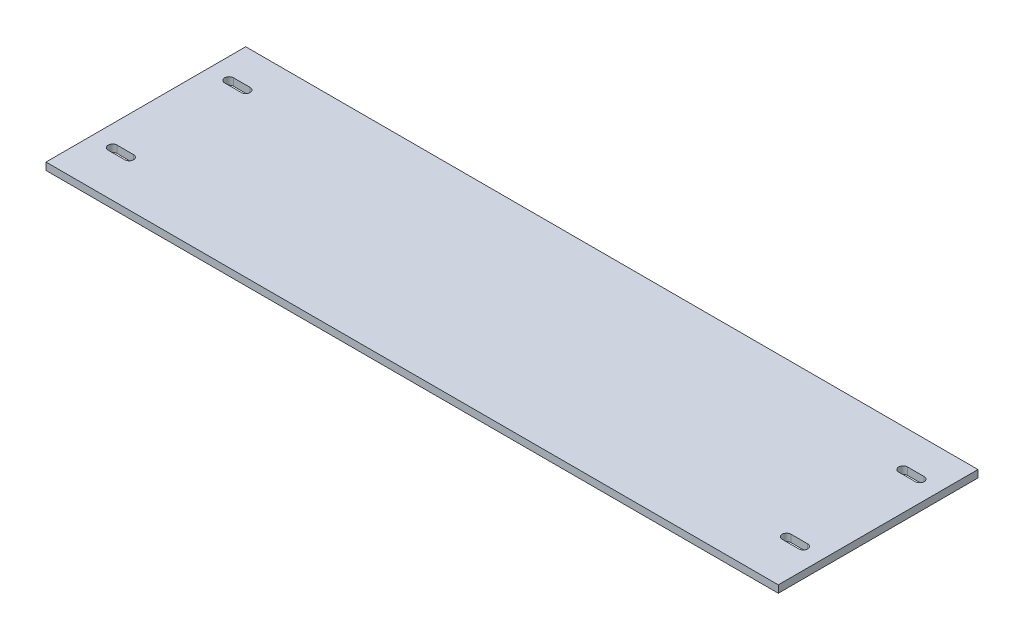
SolidWorks part; units mm, degrees
material "PC High Viscosity"
ref_plane "Front" through (0, 0, 0) normal (0, 0, 1) x (1, 0, 0)
ref_plane "Top" through (0, 0, 0) normal (0, 1, 0) x (1, 0, 0)
ref_plane "Right" through (0, 0, 0) normal (1, 0, 0) x (0, 0, -1)
sketch "Sketch1" plane through (0, 0, 0) normal (0, 1, 0) x (1, 0, 0)
  line L0 (15.875, 34.925) -> (28.575, 34.925) construction
  line L1 (0, 0) -> (558.8, 0)
  line L2 (0, 0) -> (0, 152.4)
  line L3 (0, 152.4) -> (558.8, 152.4)
  line L4 (558.8, 0) -> (558.8, 152.4)
  line L5 (15.875, 38.3032) -> (28.575, 38.3032)
  line L6 (15.875, 31.5468) -> (28.575, 31.5468)
  line L7 (22.225, 34.925) -> (22.225, 123.825) construction
  line L8 (15.875, 123.825) -> (28.575, 123.825) construction
  line L9 (15.875, 127.2032) -> (28.575, 127.2032)
  line L10 (15.875, 120.4468) -> (28.575, 120.4468)
  line L11 (22.225, 123.825) -> (66.675, 123.825) construction
  line L12 (66.675, 123.825) -> (66.675, 34.925) construction
  line L13 (66.675, 34.925) -> (22.225, 34.925) construction
  line L14 (60.325, 123.825) -> (73.025, 123.825) construction
  line L15 (60.325, 127.2032) -> (73.025, 127.2032) construction
  line L16 (60.325, 120.4468) -> (73.025, 120.4468) construction
  line L17 (60.325, 34.925) -> (73.025, 34.925) construction
  line L18 (60.325, 38.3032) -> (73.025, 38.3032) construction
  line L19 (60.325, 31.5468) -> (73.025, 31.5468) construction
  line L20 (536.575, 123.825) -> (536.575, 34.925) construction
  line L21 (542.925, 123.825) -> (530.225, 123.825) construction
  line L22 (542.925, 120.4468) -> (530.225, 120.4468)
  line L23 (542.925, 127.2032) -> (530.225, 127.2032)
  line L24 (542.925, 34.925) -> (530.225, 34.925) construction
  line L25 (542.925, 31.5468) -> (530.225, 31.5468)
  line L26 (542.925, 38.3032) -> (530.225, 38.3032)
  arc A0 (15.875, 38.3032) -> (15.875, 31.5468) centre (15.875, 34.925) ccw
  arc A1 (28.575, 31.5468) -> (28.575, 38.3032) centre (28.575, 34.925) ccw
  arc A2 (15.875, 127.2032) -> (15.875, 120.4468) centre (15.875, 123.825) ccw
  arc A3 (28.575, 120.4468) -> (28.575, 127.2032) centre (28.575, 123.825) ccw
  arc A4 (60.325, 127.2032) -> (60.325, 120.4468) centre (60.325, 123.825) ccw construction
  arc A5 (73.025, 120.4468) -> (73.025, 127.2032) centre (73.025, 123.825) ccw construction
  arc A6 (60.325, 38.3032) -> (60.325, 31.5468) centre (60.325, 34.925) ccw construction
  arc A7 (73.025, 31.5468) -> (73.025, 38.3032) centre (73.025, 34.925) ccw construction
  arc A8 (542.925, 120.4468) -> (542.925, 127.2032) centre (542.925, 123.825) ccw
  arc A9 (530.225, 127.2032) -> (530.225, 120.4468) centre (530.225, 123.825) ccw
  arc A10 (542.925, 31.5468) -> (542.925, 38.3032) centre (542.925, 34.925) ccw
  arc A11 (530.225, 38.3032) -> (530.225, 31.5468) centre (530.225, 34.925) ccw
  point P7 (22.225, 34.925)
  point P13 (22.225, 123.825)
  point P25 (66.675, 123.825)
  point P31 (66.675, 34.925)
  point P40 (536.575, 123.825)
  point P47 (536.575, 34.925)
  dimension "D1" = 6.7564
  dimension "D2" = 34.925
  dimension "D3" = 12.7
  dimension "D4" = 22.225
  dimension "D5" = 152.4
  dimension "D6" = 28.575
  dimension "D7" = 44.45
  dimension "D8" = 22.225
  dimension "D9" = 514.35
extrude "Boss-Extrude1" add sketch "Sketch1" along normal blind 5.588
fillet "Fillet1" [suppressed] radius 3.175
sketch "Sketch2" plane through (0, 5.588, 0) normal (0, 1, 0) x (1, 0, 0)
  line L0 (279.4, 152.4) -> (279.4, 0) construction
  line L1 (558.8, 152.4) -> (0, 152.4) construction
  line L2 (0, 0) -> (558.8, 0) construction
  line L4 (469.9, 25.4) -> (88.9, 25.4) construction
  line L5 (469.9, 25.4) -> (469.9, 127) construction
  line L6 (469.9, 127) -> (88.9, 127) construction
  line L7 (88.9, 25.4) -> (88.9, 127) construction
  line L8 (469.9, 25.4) -> (88.9, 127) construction
  line L9 (469.9, 127) -> (88.9, 25.4) construction
  circle A1 centre (88.9, 25.4) radius 3.3782
  circle A2 centre (469.9, 25.4) radius 3.3782
  point P6 (279.4, 76.2)
  dimension "D3" = 6.7564
  dimension "D1" = 25.4
  dimension "D2" = 381
extrude "Cut-Extrude1" [suppressed] cut sketch "Sketch2" against normal through all
